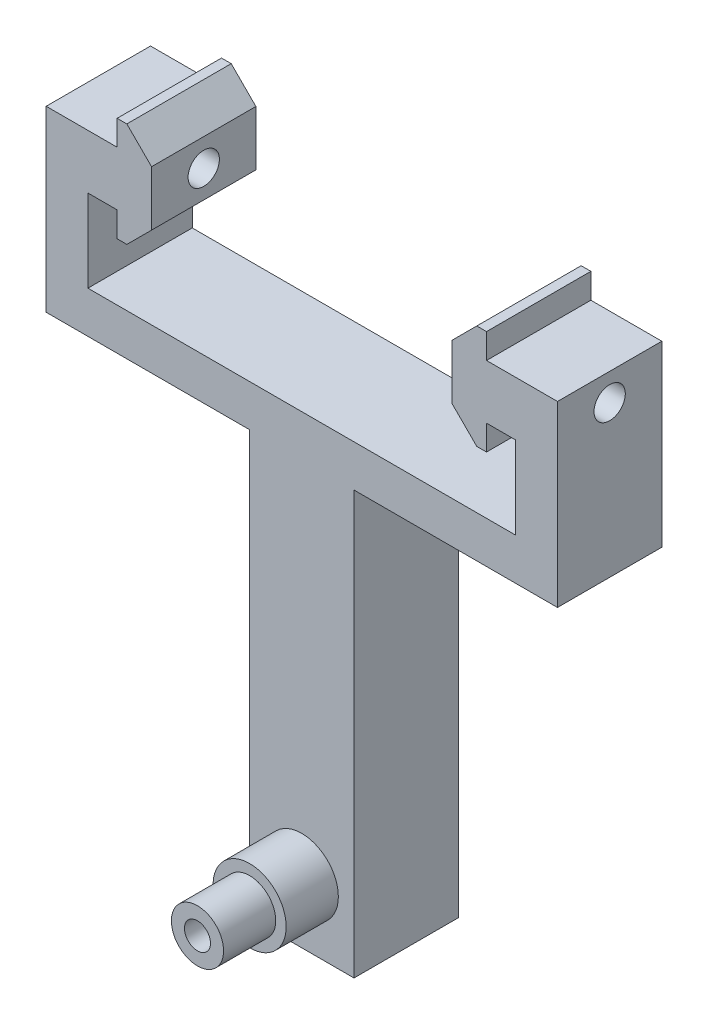
SolidWorks part; units mm, degrees
ref_plane "Front Plane" through (0, 0, 0) normal (0, 0, 1) x (1, 0, 0)
ref_plane "Top Plane" through (0, 0, 0) normal (0, 1, 0) x (1, 0, 0)
ref_plane "Right Plane" through (0, 0, 0) normal (1, 0, 0) x (0, 0, -1)
sketch "Sketch1" plane through (0, 0, 0) normal (0, 0, 1) x (1, 0, 0)
  line L0 (-14.5, 2.6) -> (-7.7, 2.6)
  line L1 (-7.7, 2.6) -> (-7.7, 5)
  line L2 (-7.7, 5) -> (-6.7678, 5)
  line L3 (-6.7678, 5) -> (-4.4, 2.6322)
  line L4 (-4.4, 2.6322) -> (-4.4, -2.6322)
  line L5 (-4.4, -2.6322) -> (-6.7678, -5)
  line L6 (-6.7678, -5) -> (-7.7, -5)
  line L7 (-7.7, -5) -> (-7.7, -2.6)
  line L8 (-7.7, -2.6) -> (-10.5, -2.6)
  line L9 (-10.5, -2.6) -> (-10.5, -10.5)
  line L10 (-10.5, -10.5) -> (30.5, -10.5)
  line L12 (5, -55) -> (15, -55)
  line L16 (-14.5, 2.6) -> (-14.5, -14.5)
  line L17 (-3.9, 2.7565) -> (-3.9, -2.7565) construction
  line L18 (-3.9586, -2.8979) -> (-6.5607, -5.5) construction
  line L19 (-3.9586, 2.8979) -> (-6.5607, 5.5) construction
  line L20 (-6.5607, 5.5) -> (-8, 5.5) construction
  line L21 (-8.2, 5.3) -> (-8.2, 3.1) construction
  line L22 (-8.2, 3.1) -> (-9.3, 3.1) construction
  line L23 (-8.2, -5.3) -> (-8.2, -3.1) construction
  line L24 (-6.5607, -5.5) -> (-8, -5.5) construction
  line L25 (-8.2, -3.1) -> (-9.3, -3.1) construction
  line L26 (-10, -3.8) -> (-10, -8.5) construction
  line L27 (-14.5, -14.5) -> (5, -14.5)
  line L28 (10, 10) -> (10, -10) construction
  line L29 (-8.5, -10) -> (-3.8, -10) construction
  line L30 (5, -14.5) -> (5, -55)
  line L31 (3.8, -10) -> (8.5, -10) construction
  line L34 (8.5, 10) -> (11.5, 10) construction
  line L35 (8.5, -10) -> (11.5, -10) construction
  line L36 (30.5, -2.6) -> (30.5, -10.5)
  line L37 (27.7, -2.6) -> (30.5, -2.6)
  line L38 (27.7, -5) -> (27.7, -2.6)
  line L39 (26.7678, -5) -> (27.7, -5)
  line L40 (24.4, -2.6322) -> (26.7678, -5)
  line L41 (24.4, 2.6322) -> (24.4, -2.6322)
  line L42 (26.7678, 5) -> (24.4, 2.6322)
  line L43 (27.7, 5) -> (26.7678, 5)
  line L44 (27.7, 2.6) -> (27.7, 5)
  line L45 (34.5, 2.6) -> (27.7, 2.6)
  line L46 (34.5, 2.6) -> (34.5, -14.5)
  line L47 (34.5, -14.5) -> (15, -14.5)
  line L48 (15, -14.5) -> (15, -55)
  dimension "D1" = 0.5
  dimension "D2" = 0.5
  dimension "D3" = 0.5
  dimension "D4" = 0.5
  dimension "D5" = 0.5
  dimension "D6" = 0.5
  dimension "D7" = 0.5
  dimension "D8" = 0.5
  dimension "D9" = 0.5
  dimension "D10" = 0.5
  dimension "D11" = 4
  dimension "D12" = 0.5
  dimension "D13" = 4
  dimension "D14" = 5
  dimension "D16" = 45
extrude "Boss-Extrude1" add sketch "Sketch1" along normal blind 10
sketch "Sketch2" plane through (-14.5, 0, 0) normal (-1, 0, 0) x (0, 0, 1)
  line L1 (10, -14.5) -> (0, -14.5) construction
  line L4 (10, -2.6322) -> (10, 2.6322) construction
  circle A0 centre (5, 0) radius 1.5
  point P4 (5, -14.5)
  point P7 (10, 0)
  dimension "D1" = 0
  dimension "D2" = 3
  dimension "D3" = 0
extrude "Cut-Extrude1" cut sketch "Sketch2" against normal blind 13
sketch "Sketch3" plane through (34.5, 0, 0) normal (1, 0, 0) x (0, 0, -1)
  line L0 (-10, 2.6322) -> (-10, -2.6322) construction
  line L1 (-10, -14.5) -> (0, -14.5) construction
  circle A0 centre (-5, 0) radius 1.5
  point P4 (-10, 0)
  point P7 (-5, -14.5)
  dimension "D1" = 0
  dimension "D2" = 0
  dimension "D3" = 3
extrude "Cut-Extrude2" cut sketch "Sketch3" against normal blind 13
sketch "Sketch4" plane through (0, 0, 10) normal (0, 0, 1) x (1, 0, 0)
  line L0 (5, -55) -> (15, -55) construction
  line L1 (30.5, -10.5) -> (-10.5, -10.5) construction
  circle A0 centre (10, -49) radius 2.5
  point P4 (10, -55)
  dimension "D1" = 0
  dimension "D2" = 38.5
  dimension "D3" = 5
extrude "Boss-Extrude2" add sketch "Sketch4" along normal blind 10
sketch "Sketch5" plane through (0, 0, 10) normal (0, 0, 1) x (1, 0, 0)
  circle A1 centre (10, -49) radius 3.5
  dimension "D1" = 7
extrude "Boss-Extrude3" add sketch "Sketch5" along normal blind 5
sketch "Sketch6" plane through (0, 0, 20) normal (0, 0, 1) x (1, 0, 0)
  circle A0 centre (10, -49) radius 1.25
  dimension "D1" = 2.5
extrude "Cut-Extrude3" cut sketch "Sketch6" against normal blind 4
